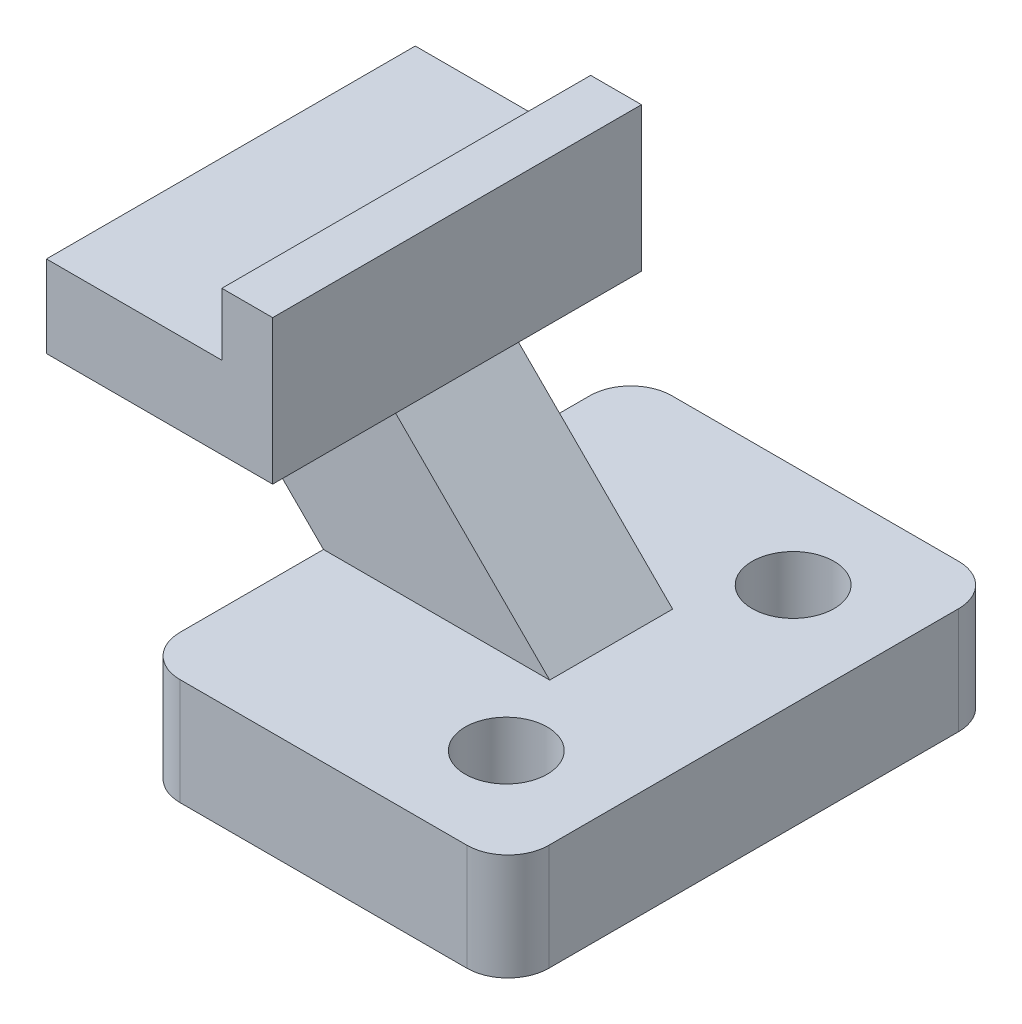
SolidWorks part; units mm, degrees
ref_plane "Alzado" through (0, 0, 0) normal (0, 0, 1) x (1, 0, 0)
ref_plane "Planta" through (0, 0, 0) normal (0, 1, 0) x (1, 0, 0)
ref_plane "Vista lateral" through (0, 0, 0) normal (1, 0, 0) x (0, 0, -1)
sketch "Croquis1" plane through (0, 0, 0) normal (0, 1, 0) x (1, 0, 0)
  line L1 (-0.875, 1.5) -> (0.875, 1.5)
  line L2 (-1.125, 1.25) -> (-1.125, -1.25)
  line L3 (-0.875, -1.5) -> (0.875, -1.5)
  line L4 (1.125, 1.25) -> (1.125, -1.25)
  arc A0 (-1.125, -1.25) -> (-0.875, -1.5) centre (-0.875, -1.25) ccw
  arc A1 (0.875, -1.5) -> (1.125, -1.25) centre (0.875, -1.25) ccw
  arc A2 (1.125, 1.25) -> (0.875, 1.5) centre (0.875, 1.25) ccw
  arc A3 (-0.875, 1.5) -> (-1.125, 1.25) centre (-0.875, 1.25) ccw
  circle A4 centre (0.495, 0.87) radius 0.25
  circle A5 centre (0.495, -0.88) radius 0.25
  point P6 (-1.125, -1.5)
  point P9 (1.125, -1.5)
  point P12 (1.125, 1.5)
  point P17 (0, 1.5)
  point P20 (1.125, 0)
  dimension "D3" = 0.25
  dimension "D4" = 1.75
  dimension "D7" = 0.5
  dimension "D1" = 3
  dimension "D2" = 2.25
  dimension "D5" = 0.63
  dimension "D6" = 0.63
extrude "Saliente-Extruir2" add sketch "Croquis1" along normal blind 0.65
ref_plane "Plano2" through (0, 0, 0) normal (0, 0, 1) x (1, 0, 0)
sketch "Croquis6" plane through (0, 0, 0) normal (0, 0, 1) x (1, 0, 0)
  line L0 (-1.125, 0.65) -> (-2.065, 1.59)
  line L2 (-0.685, 1.59) -> (0.255, 0.65)
  line L3 (-0.875, 0.65) -> (0.875, 0.65) construction
  line L4 (-1.125, 0.65) -> (0.255, 0.65)
  line L5 (-0.685, 1.59) -> (-0.685, 2.47)
  line L6 (-0.685, 2.47) -> (-0.995, 2.47)
  line L7 (-0.995, 2.47) -> (-0.995, 2.09)
  line L8 (-0.995, 2.09) -> (-2.065, 2.09)
  line L9 (-2.065, 2.09) -> (-2.065, 1.59)
  point P3 (0, 0)
  point P13 (0, 0)
  point P14 (0, 0)
  point P15 (-1.4155, 1.59)
  point P16 (0, 0)
  dimension "D1" = 135
  dimension "D2" = 1.38
  dimension "D3" = 0.5
  dimension "D4" = 0.31
  dimension "D5" = 0.88
  dimension "D6" = 0.94
extrude "Saliente-Extruir3" add sketch "Croquis6" along normal mid plane 0.75
sketch "Croquis7" plane through (0, 0, 0) normal (0, 0, 1) x (1, 0, 0)
  line L0 (-2.065, 1.59) -> (-0.685, 1.59)
  line L1 (-0.685, 1.59) -> (-0.685, 2.47)
  line L2 (-0.685, 2.47) -> (-0.995, 2.47) construction
  line L3 (-0.685, 1.59) -> (-0.685, 2.47) construction
  line L4 (-0.685, 2.47) -> (-0.995, 2.47)
  line L5 (-0.995, 2.47) -> (-0.995, 2.09)
  line L6 (-0.995, 2.09) -> (-2.065, 2.09)
  line L7 (-2.065, 2.09) -> (-2.065, 1.59)
extrude "Saliente-Extruir4" add sketch "Croquis7" along normal mid plane 2.25
